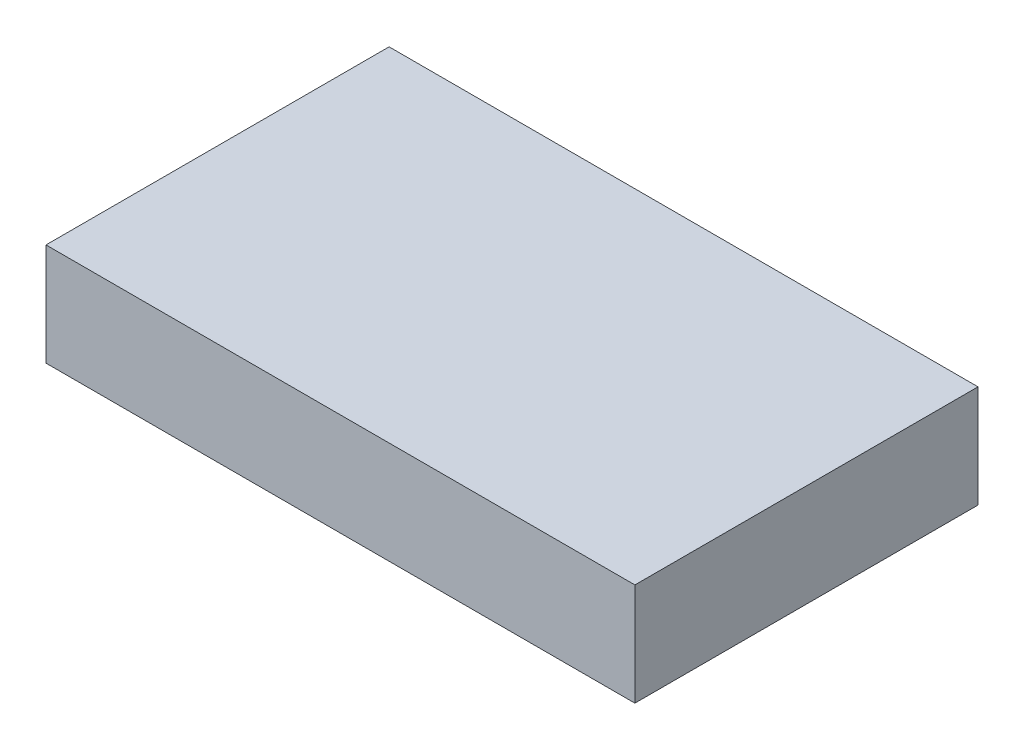
SolidWorks part; units mm, degrees
ref_plane "Front Plane" through (0, 0, 0) normal (0, 0, 1) x (1, 0, 0)
ref_plane "Top Plane" through (0, 0, 0) normal (0, 1, 0) x (1, 0, 0)
ref_plane "Right Plane" through (0, 0, 0) normal (1, 0, 0) x (0, 0, -1)
sketch "Sketch1" plane through (0, 0, 0) normal (0, 1, 0) x (1, 0, 0)
  line L1 (-57.5, -33.5) -> (57.5, -33.5)
  line L2 (-57.5, -33.5) -> (-57.5, 33.5)
  line L3 (-57.5, 33.5) -> (57.5, 33.5)
  line L4 (57.5, -33.5) -> (57.5, 33.5)
  line L5 (0, 33.5) -> (0, -33.5) construction
  line L6 (-57.5, 0) -> (57.5, 0) construction
  point P0 (0, 0)
  dimension "D1" = 115
  dimension "D2" = 67
extrude "Boss-Extrude1" add sketch "Sketch1" along normal blind 20
